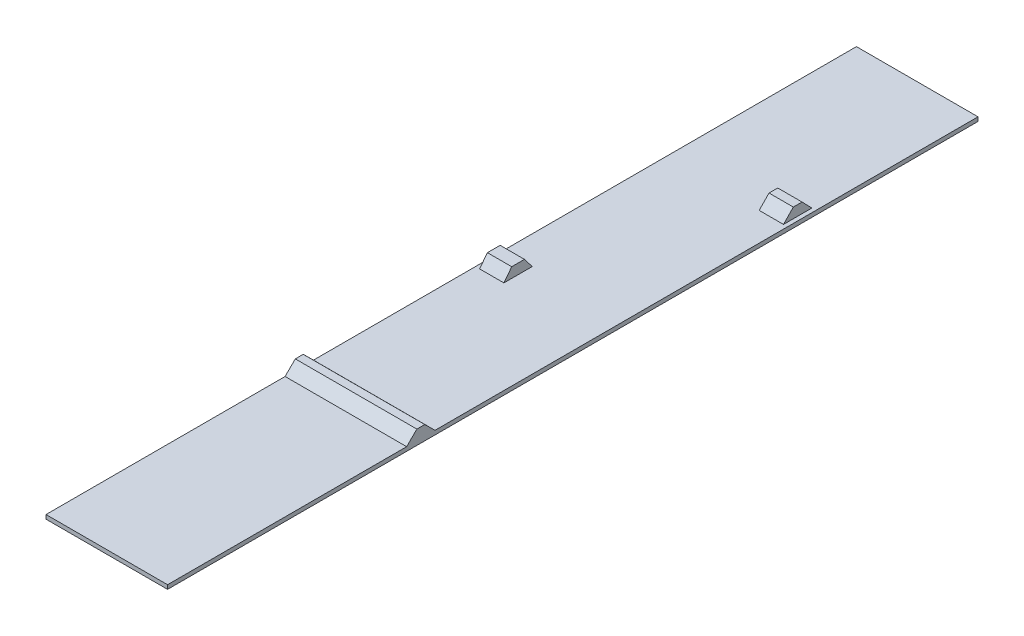
SolidWorks part; units mm, degrees
ref_plane "Front Plane" through (0, 0, 0) normal (0, 0, 1) x (1, 0, 0)
ref_plane "Top Plane" through (0, 0, 0) normal (0, 1, 0) x (1, 0, 0)
ref_plane "Right Plane" through (0, 0, 0) normal (1, 0, 0) x (0, 0, -1)
sketch "Sketch1" plane through (0, 0, 0) normal (0, 1, 0) x (1, 0, 0)
  line L1 (-150, 1000) -> (150, 1000)
  line L2 (-150, 1000) -> (-150, -1000)
  line L3 (-150, -1000) -> (150, -1000)
  line L4 (150, 1000) -> (150, -1000)
  line L5 (-150, 1000) -> (150, -1000) construction
  line L6 (-150, -1000) -> (150, 1000) construction
  point P0 (0, 0)
  dimension "D1" = 2000
  dimension "D2" = 300
extrude "Boss-Extrude1" add sketch "Sketch1" along normal blind 10
sketch "Sketch2" plane through (0, 0, 0) normal (1, 0, 0) x (0, 0, -1)
  line L0 (530, 10) -> (554.2165, 35)
  line L1 (-1000, 10) -> (1000, 10) construction
  line L2 (554.2165, 35) -> (575.7835, 35)
  line L3 (575.7835, 35) -> (600, 10)
  line L4 (600, 10) -> (530, 10)
  line L5 (1000, 10) -> (1000, 0) construction
  point P4 (565, 35)
  point P7 (565, 10)
  point P10 (554.2165, 35)
  dimension "D1" = 70
  dimension "D2" = 25
  dimension "D3" = 400
extrude "Boss-Extrude2" add sketch "Sketch2" along normal blind 60 from offset 80
sketch "Sketch3" plane through (0, 0, 0) normal (1, 0, 0) x (0, 0, -1)
  line L0 (60, 10) -> (79.2783, 35)
  line L1 (-1000, 10) -> (1000, 10) construction
  line L2 (79.2783, 35) -> (110.7217, 35)
  line L3 (110.7217, 35) -> (130, 10)
  line L4 (130, 10) -> (60, 10)
  point P4 (95, 35)
  point P7 (95, 10)
  point P9 (79.2783, 35)
  dimension "D1" = 70
  dimension "D2" = 25
  dimension "D3" = 400
extrude "Boss-Extrude3" add sketch "Sketch3" along normal blind 60 from offset 140 offset against normal yes
sketch "Sketch4" plane through (0, 0, 0) normal (1, 0, 0) x (0, 0, -1)
  line L0 (-410, 10) -> (-384.7719, 35)
  line L1 (-1000, 10) -> (1000, 10) construction
  line L2 (-384.7719, 35) -> (-365.2281, 35)
  line L3 (-365.2281, 35) -> (-340, 10)
  line L4 (-340, 10) -> (-410, 10)
  point P4 (-375, 10)
  point P7 (-375, 35)
  dimension "D1" = 400
  dimension "D2" = 70
  dimension "D3" = 25
extrude "Boss-Extrude4" add sketch "Sketch4" along normal blind 150 and the other way blind 150
